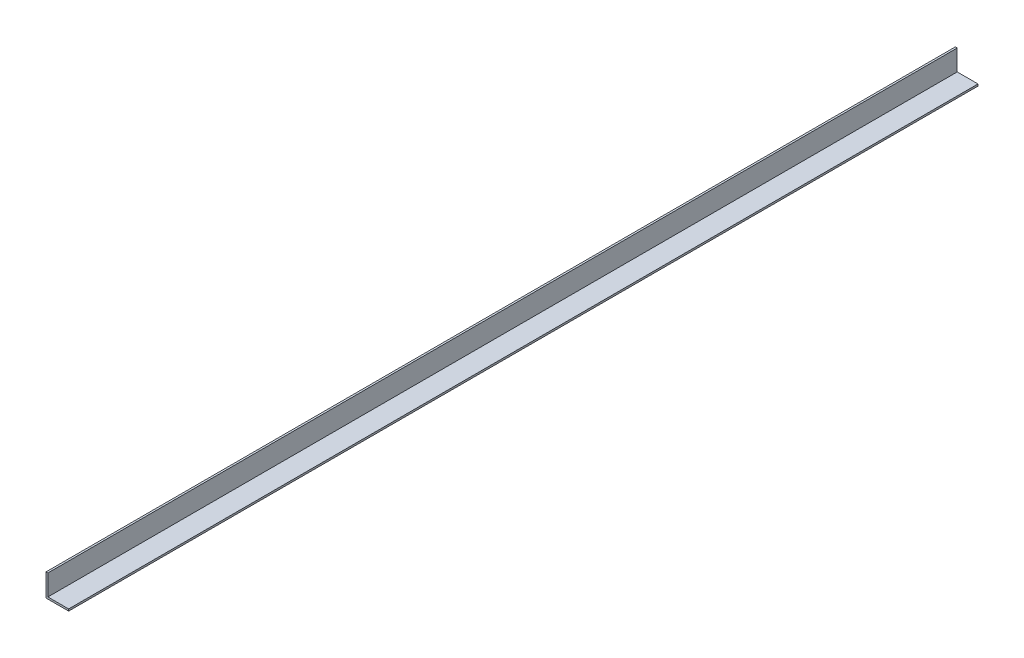
SolidWorks part; units mm, degrees
material "ASTM A36 Acero"
ref_plane "Alzado" through (0, 0, 0) normal (0, 0, 1) x (1, 0, 0)
ref_plane "Planta" through (0, 0, 0) normal (0, 1, 0) x (1, 0, 0)
ref_plane "Vista lateral" through (0, 0, 0) normal (1, 0, 0) x (0, 0, -1)
sketch "Croquis1" plane through (0, 0, 0) normal (0, 0, 1) x (1, 0, 0)
  line L0 (0, 152) -> (0, 0)
  line L1 (0, 0) -> (152, 0)
  line L2 (152, 0) -> (152, 12.7)
  line L3 (152, 12.7) -> (12.7, 12.7)
  line L4 (12.7, 12.7) -> (12.7, 152)
  line L5 (12.7, 152) -> (0, 152)
  dimension "D1" = 12.7
  dimension "D2" = 152
extrude "Saliente-Extruir1" add sketch "Croquis1" against normal blind 6100
